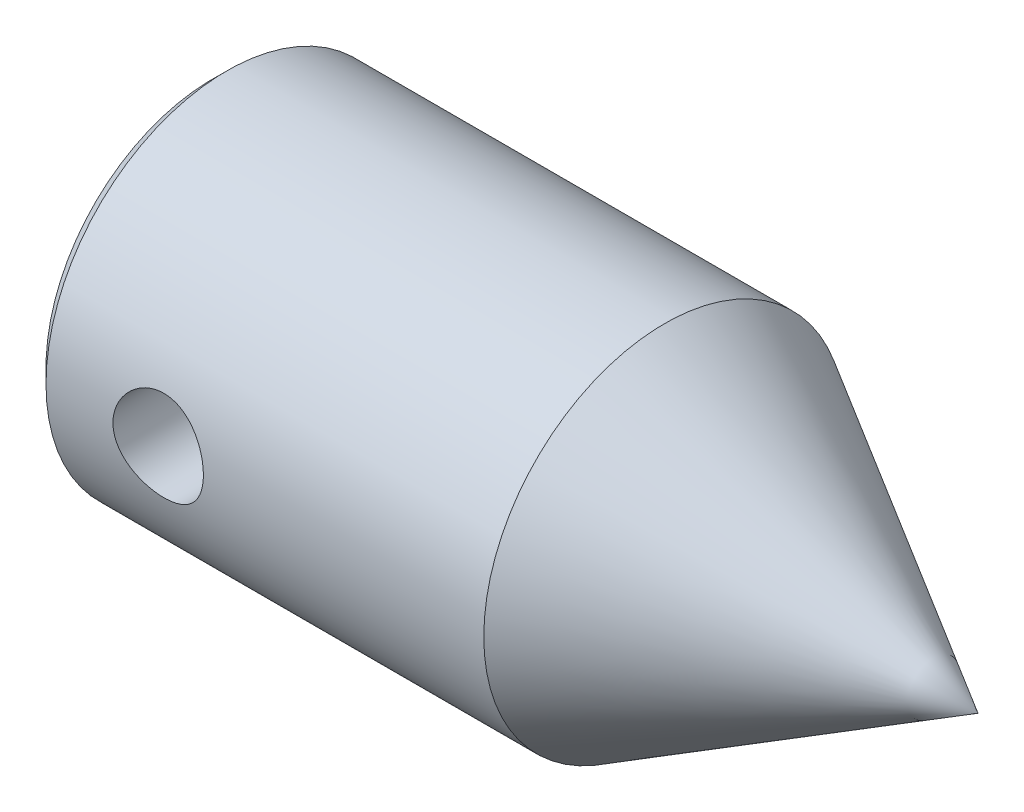
SolidWorks part; units mm, degrees
ref_plane "Front" through (0, 0, 0) normal (0, 0, 1) x (1, 0, 0)
ref_plane "Top" through (0, 0, 0) normal (0, 1, 0) x (1, 0, 0)
ref_plane "Right" through (0, 0, 0) normal (1, 0, 0) x (0, 0, -1)
sketch "Sketch1" plane through (0, 0, 0) normal (0, 0, 1) x (1, 0, 0)
  line L0 (0, 0) -> (53.747, 0) construction
  line L1 (0, 12.7) -> (31.75, 12.7)
  line L2 (31.75, 12.7) -> (53.747, 0)
  line L3 (0, 12.7) -> (0, 7.9375)
  line L4 (0, 7.9375) -> (25.4, 7.9375)
  line L5 (33.3375, 0) -> (53.747, 0) construction
  line L6 (0, 0) -> (0, 7.9375) construction
  line L7 (33.3375, 0) -> (53.747, 0)
  line L8 (25.4, 7.9375) -> (33.3375, 0)
  dimension "D1" = 30
  dimension "D2" = 12.7
  dimension "D3" = 45
  dimension "D4" = 7.9375
  dimension "D5" = 31.75
  dimension "D6" = 25.4
revolve "Revolve1" add sketch "Sketch1" angle 360 about L0
sketch "Sketch2" plane through (0, 0, 0) normal (0, 0, 1) x (1, 0, 0)
  line L0 (0, 0) -> (8.89, 0) construction
  circle A0 centre (8.89, 0) radius 3.175
  dimension "D1" = 6.35
  dimension "D2" = 8.89
extrude "Cut-Extrude1" cut sketch "Sketch2" along normal through all
chamfer "Chamfer1" distance 1.016 angle 45 2 edges at (0, 0, 12.7) (0, 0, 7.9375)
